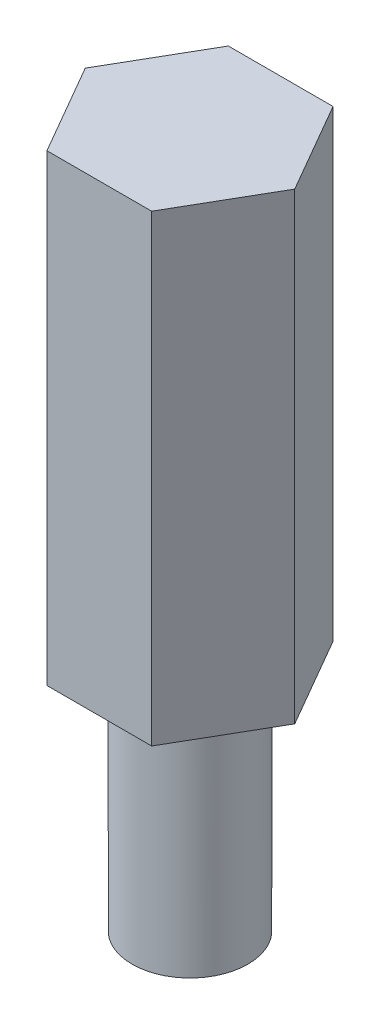
SolidWorks part; units mm, degrees
ref_plane "前视基准面" through (0, 0, 0) normal (0, 0, 1) x (1, 0, 0)
ref_plane "上视基准面" through (0, 0, 0) normal (0, 1, 0) x (1, 0, 0)
ref_plane "右视基准面" through (0, 0, 0) normal (1, 0, 0) x (0, 0, -1)
sketch "草图1" plane through (0, 0, 0) normal (0, 1, 0) x (1, 0, 0)
  line L1 (-1.3568, 2.35) -> (-2.7135, 0)
  line L2 (-2.7135, 0) -> (-1.3568, -2.35)
  line L3 (-1.3568, -2.35) -> (1.3568, -2.35)
  line L4 (1.3568, -2.35) -> (2.7135, 0)
  line L5 (2.7135, 0) -> (1.3568, 2.35)
  line L6 (1.3568, 2.35) -> (-1.3568, 2.35)
  circle A0 centre (0, 0) radius 2.35 construction
  dimension "D1" = 4.7
extrude "凸台-拉伸1" add sketch "草图1" along normal blind 12
sketch "草图2" plane through (0, 0, 0) normal (0, -1, 0) x (1, 0, 0)
  circle A0 centre (0, 0) radius 1.5
  dimension "D1" = 3
extrude "凸台-拉伸2" add sketch "草图2" along normal blind 6
